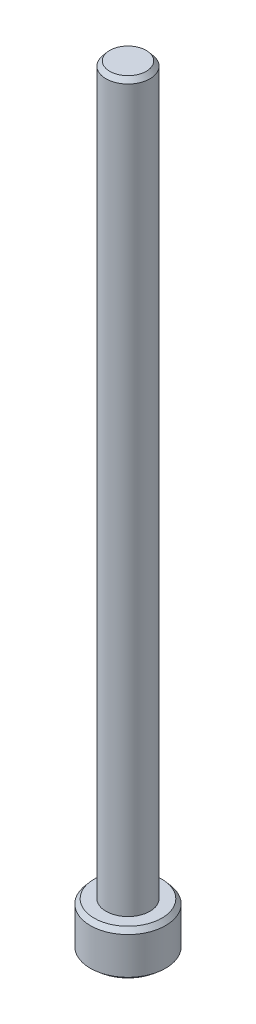
SolidWorks part; units mm, degrees
ref_plane "Front Plane" through (0, 0, 0) normal (0, 0, 1) x (1, 0, 0)
ref_plane "Top Plane" through (0, 0, 0) normal (0, 1, 0) x (1, 0, 0)
ref_plane "Right Plane" through (0, 0, 0) normal (1, 0, 0) x (0, 0, -1)
sketch "Sketch1" plane through (0, 0, 0) normal (0, 1, 0) x (1, 0, 0)
  circle A0 centre (0, 0) radius 4.15
  dimension "D1" = 8.3
extrude "Boss-Extrude1" add sketch "Sketch1" along normal blind 5
sketch "Sketch2" plane through (0, 5, 0) normal (0, 1, 0) x (1, 0, 0)
  circle A0 centre (0, 0) radius 2.425
  dimension "D1" = 4.85
extrude "Boss-Extrude2" add sketch "Sketch2" along normal blind 80
sketch "Sketch3" plane through (0, 0, 0) normal (0, -1, 0) x (1, 0, 0)
  line L1 (0, 2.786) -> (-2.4128, 1.393)
  line L2 (-2.4128, 1.393) -> (-2.4128, -1.393)
  line L3 (-2.4128, -1.393) -> (0, -2.786)
  line L4 (0, -2.786) -> (2.4128, -1.393)
  line L5 (2.4128, -1.393) -> (2.4128, 1.393)
  line L6 (2.4128, 1.393) -> (0, 2.786)
  circle A0 centre (0, 0) radius 2.4128 construction
extrude "Cut-Extrude1" cut sketch "Sketch3" against normal blind 3
chamfer "Chamfer1" distance 0.5 angle 40 3 edges at (0, 0, 4.15) (0, 5, 4.15) (0, 85, 2.425)
